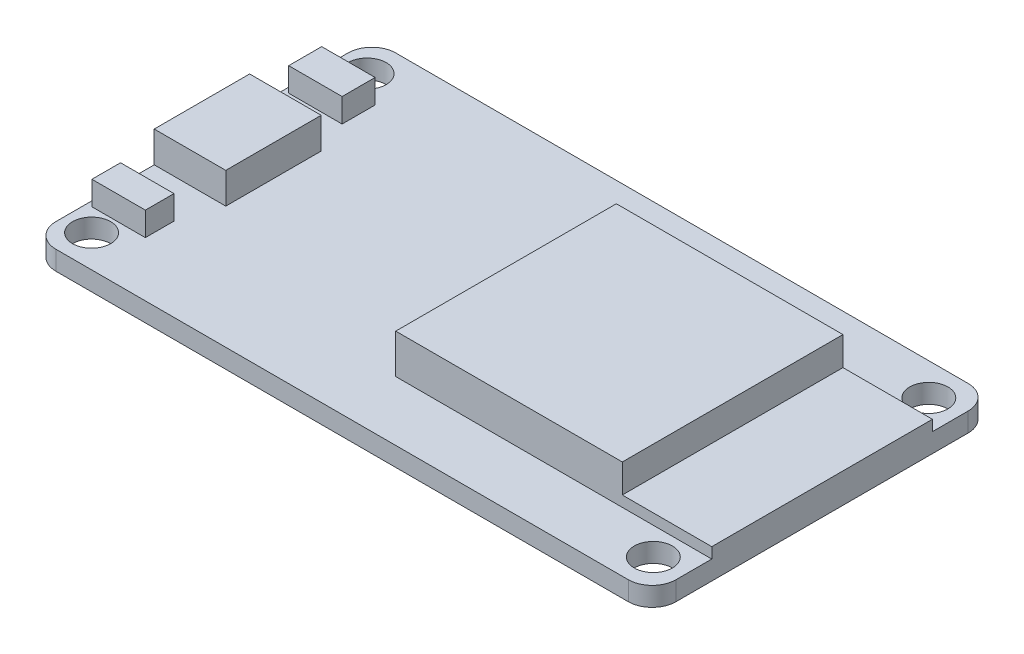
SolidWorks part; units mm, degrees
ref_plane "Front Plane" through (0, 0, 0) normal (0, 0, 1) x (1, 0, 0)
ref_plane "Top Plane" through (0, 0, 0) normal (0, 1, 0) x (1, 0, 0)
ref_plane "Right Plane" through (0, 0, 0) normal (1, 0, 0) x (0, 0, -1)
sketch "Sketch1" plane through (0, 0, 0) normal (0, 1, 0) x (1, 0, 0)
  line L1 (26, -14.25) -> (-26, -14.25)
  line L2 (26, -14.25) -> (26, 14.25)
  line L3 (26, 14.25) -> (-26, 14.25)
  line L4 (-26, -14.25) -> (-26, 14.25)
  line L5 (26, -14.25) -> (-26, 14.25) construction
  line L6 (26, 14.25) -> (-26, -14.25) construction
  line L7 (-23.7, -11.55) -> (23.4, -11.55) construction
  line L8 (-23.7, -11.55) -> (-23.7, 11.55) construction
  line L9 (-23.7, 11.55) -> (23.4, 11.55) construction
  line L10 (23.4, -11.55) -> (23.4, 11.55) construction
  line L11 (-23.7, -11.55) -> (23.4, 11.55) construction
  line L12 (-23.7, 11.55) -> (23.4, -11.55) construction
  circle A0 centre (-23.7, 11.55) radius 1.6
  circle A1 centre (-23.7, -11.55) radius 1.6
  circle A2 centre (23.4, 11.55) radius 1.6
  circle A3 centre (23.4, -11.55) radius 1.6
  point P0 (0, 0)
  point P10 (-0.15, 0)
  dimension "D3" = 3.2
  dimension "D1" = 52
  dimension "D2" = 28.5
  dimension "D4" = 2.3
  dimension "D5" = 2.6
  dimension "D6" = 2.7
extrude "Boss-Extrude1" add sketch "Sketch1" along normal blind 1.6
fillet "Fillet1" radius 2 4 edges at (26, 0.8, -14.25) (26, 0.8, 14.25) (-26, 0.8, -14.25) (-26, 0.8, 14.25)
sketch "Sketch2" plane through (0, 1.6, 0) normal (0, 1, 0) x (1, 0, 0)
  line L0 (-26, 12.25) -> (-26, -12.25) construction
  line L1 (-26, -4) -> (-20, -4)
  line L2 (-26, -4) -> (-26, 4)
  line L3 (-26, 4) -> (-20, 4)
  line L4 (-20, -4) -> (-20, 4)
  point P7 (-26, 0)
  point P8 (-26, 0)
  dimension "D1" = 8
  dimension "D2" = 6
extrude "Boss-Extrude2" add sketch "Sketch2" along normal blind 2.6
sketch "Sketch3" plane through (0, 1.6, 0) normal (0, 1, 0) x (1, 0, 0)
  line L0 (26, -12.25) -> (26, 12.25) construction
  line L1 (26, -9.25) -> (-0.5, -9.25)
  line L2 (26, -9.25) -> (26, 9.25)
  line L3 (26, 9.25) -> (-0.5, 9.25)
  line L4 (-0.5, -9.25) -> (-0.5, 9.25)
  point P6 (26, 0)
  point P7 (26, 0)
  dimension "D1" = 18.5
  dimension "D2" = 26.5
extrude "Boss-Extrude3" add sketch "Sketch3" along normal blind 0.9
sketch "Sketch4" plane through (0, 2.5, 0) normal (0, 1, 0) x (1, 0, 0)
  line L0 (-0.5, -9.25) -> (26, -9.25) construction
  line L1 (-0.5, 9.25) -> (18.5, 9.25)
  line L2 (-0.5, 9.25) -> (-0.5, -9.25)
  line L3 (-0.5, -9.25) -> (18.5, -9.25)
  line L4 (18.5, 9.25) -> (18.5, -9.25)
  dimension "D1" = 19
extrude "Boss-Extrude4" add sketch "Sketch4" along normal blind 2.4
sketch "Sketch5" plane through (0, 1.6, 0) normal (0, 1, 0) x (1, 0, 0)
  line L1 (-25.5638, 9.6062) -> (-21.0835, 9.6062)
  line L2 (-25.5638, 9.6062) -> (-25.5638, 6.839)
  line L3 (-25.5638, 6.839) -> (-21.0835, 6.839)
  line L4 (-21.0835, 9.6062) -> (-21.0835, 6.839)
  line L5 (-25.5638, -7.2606) -> (-21.0835, -7.2606)
  line L6 (-25.5638, -7.2606) -> (-25.5638, -9.6589)
  line L7 (-25.5638, -9.6589) -> (-21.0835, -9.6589)
  line L8 (-21.0835, -7.2606) -> (-21.0835, -9.6589)
extrude "Boss-Extrude5" add sketch "Sketch5" along normal blind 2
